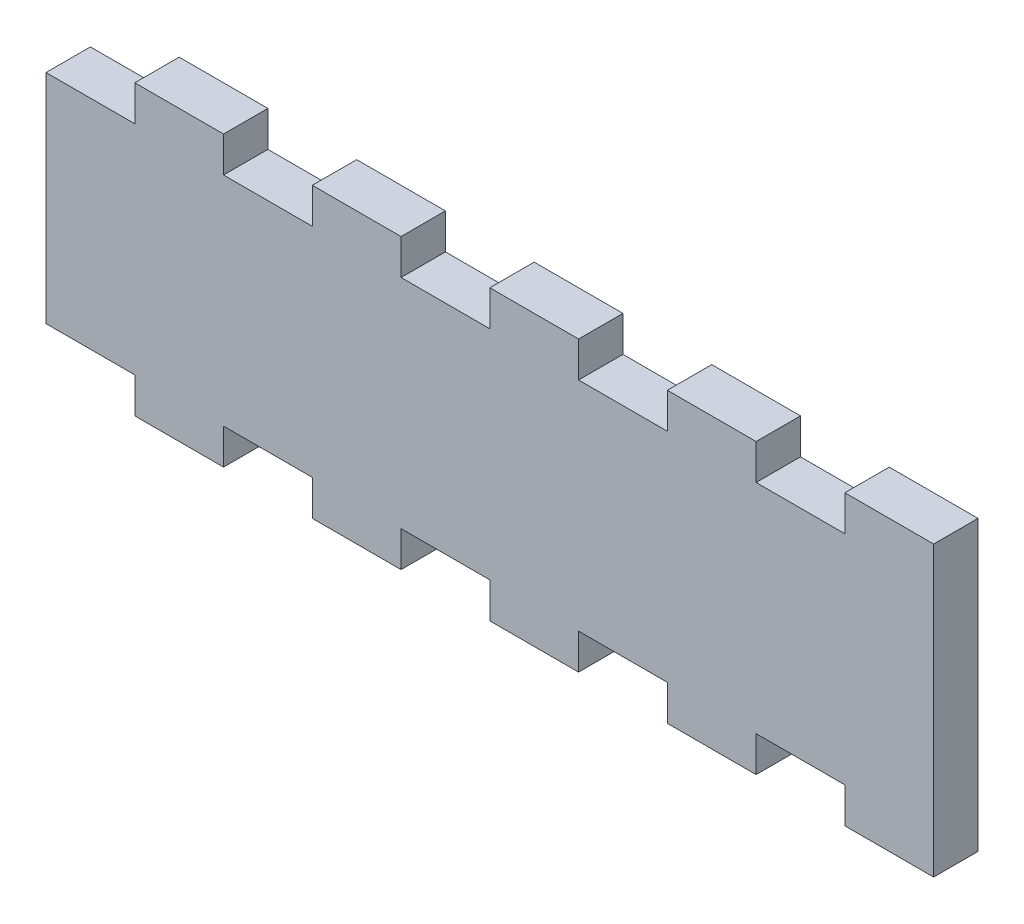
SolidWorks part; units mm, degrees
ref_plane "Front Plane" through (0, 0, 0) normal (0, 0, 1) x (1, 0, 0)
ref_plane "Top Plane" through (0, 0, 0) normal (0, 1, 0) x (1, 0, 0)
ref_plane "Right Plane" through (0, 0, 0) normal (1, 0, 0) x (0, 0, -1)
sketch "Sketch1" plane through (0, 0, 0) normal (0, 0, 1) x (1, 0, 0)
  line L1 (-106.5398, 55.2913) -> (93.4602, 55.2913)
  line L2 (-106.5398, 55.2913) -> (-106.5398, -9.7087)
  line L3 (-106.5398, -9.7087) -> (93.4602, -9.7087)
  line L4 (93.4602, 55.2913) -> (93.4602, -9.7087)
  dimension "D1" = 200
  dimension "D2" = 65
extrude "Boss-Extrude1" add sketch "Sketch1" along normal blind 10
sketch "Sketch2" plane through (0, 0, 10) normal (0, 0, 1) x (1, 0, 0)
  line L0 (-66.5398, 55.2913) -> (-66.5398, 47.2913)
  line L1 (-106.5398, 55.2913) -> (-86.5398, 55.2913)
  line L2 (-106.5398, 55.2913) -> (-106.5398, 47.2913)
  line L3 (-106.5398, 47.2913) -> (-86.5398, 47.2913)
  line L4 (-86.5398, 55.2913) -> (-86.5398, 47.2913)
  line L5 (-106.5398, -9.7087) -> (-86.5398, -9.7087)
  line L6 (-106.5398, -9.7087) -> (-106.5398, -1.7087)
  line L7 (-106.5398, -1.7087) -> (-86.5398, -1.7087)
  line L8 (-86.5398, -9.7087) -> (-86.5398, -1.7087)
  line L9 (-66.5398, 55.2913) -> (-46.5398, 55.2913)
  line L10 (-46.5398, 55.2913) -> (-46.5398, 47.2913)
  line L11 (-66.5398, 47.2913) -> (-46.5398, 47.2913)
  line L12 (-66.5398, -9.7087) -> (-66.5398, -1.7087)
  line L13 (-66.5398, -9.7087) -> (-46.5398, -9.7087)
  line L14 (-46.5398, -9.7087) -> (-46.5398, -1.7087)
  line L15 (-66.5398, -1.7087) -> (-46.5398, -1.7087)
  line L16 (-26.5398, 55.2913) -> (-26.5398, 47.2913)
  line L17 (-26.5398, 55.2913) -> (-6.5398, 55.2913)
  line L18 (-6.5398, 55.2913) -> (-6.5398, 47.2913)
  line L19 (-26.5398, 47.2913) -> (-6.5398, 47.2913)
  line L20 (-26.5398, -9.7087) -> (-26.5398, -1.7087)
  line L21 (-26.5398, -9.7087) -> (-6.5398, -9.7087)
  line L22 (-6.5398, -9.7087) -> (-6.5398, -1.7087)
  line L23 (-26.5398, -1.7087) -> (-6.5398, -1.7087)
  line L24 (13.4602, 55.2913) -> (13.4602, 47.2913)
  line L25 (13.4602, 55.2913) -> (33.4602, 55.2913)
  line L26 (33.4602, 55.2913) -> (33.4602, 47.2913)
  line L27 (13.4602, 47.2913) -> (33.4602, 47.2913)
  line L28 (13.4602, -9.7087) -> (13.4602, -1.7087)
  line L29 (13.4602, -9.7087) -> (33.4602, -9.7087)
  line L30 (33.4602, -9.7087) -> (33.4602, -1.7087)
  line L31 (13.4602, -1.7087) -> (33.4602, -1.7087)
  line L32 (53.4602, 55.2913) -> (53.4602, 47.2913)
  line L33 (53.4602, 55.2913) -> (73.4602, 55.2913)
  line L34 (73.4602, 55.2913) -> (73.4602, 47.2913)
  line L35 (53.4602, 47.2913) -> (73.4602, 47.2913)
  line L36 (53.4602, -9.7087) -> (53.4602, -1.7087)
  line L37 (53.4602, -9.7087) -> (73.4602, -9.7087)
  line L38 (73.4602, -9.7087) -> (73.4602, -1.7087)
  line L39 (53.4602, -1.7087) -> (73.4602, -1.7087)
  dimension "D1" = 20
  dimension "D2" = 8
  dimension "D3" = 5
extrude "Cut-Extrude1" cut sketch "Sketch2" against normal through all
